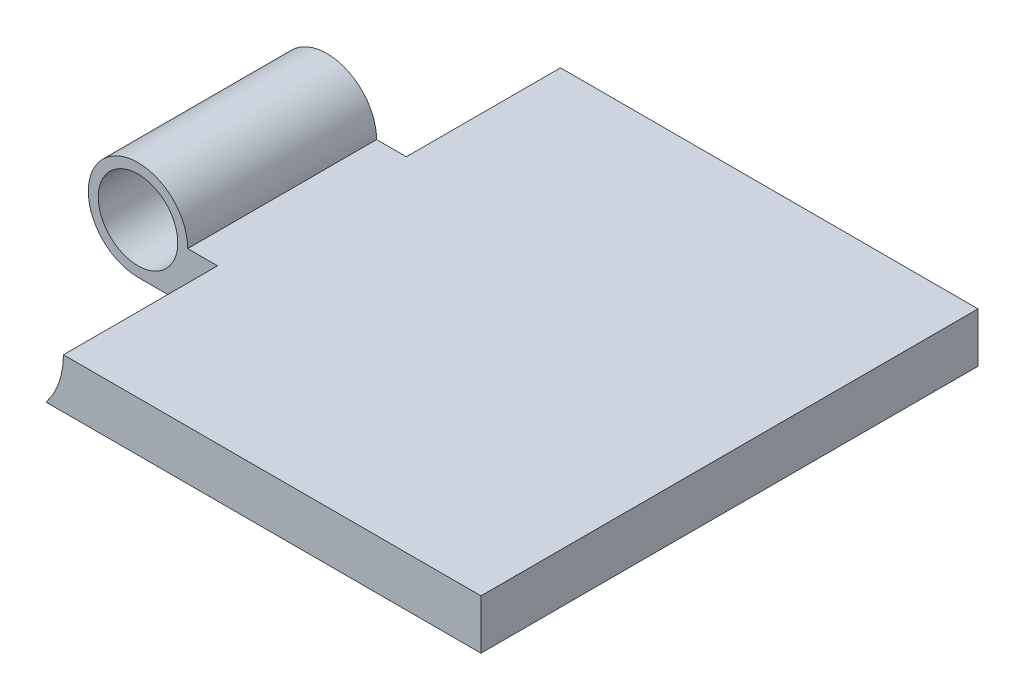
SolidWorks part; units mm, degrees
ref_plane "Front Plane" through (0, 0, 0) normal (0, 0, 1) x (1, 0, 0)
ref_plane "Top Plane" through (0, 0, 0) normal (0, 1, 0) x (1, 0, 0)
ref_plane "Right Plane" through (0, 0, 0) normal (1, 0, 0) x (0, 0, -1)
sketch "Sketch1" plane through (0, 0, 0) normal (0, 0, 1) x (1, 0, 0)
  line L1 (0, 0) -> (50, 0)
  line L2 (0, 0) -> (0, -5)
  line L3 (0, -5) -> (50, -5)
  line L4 (50, 0) -> (50, -5)
  point P5 (0, 0)
extrude "Boss-Extrude1" add sketch "Sketch1" against normal blind 50 contours L3 L4 L1 L2
sketch "Sketch2" plane through (0, 0, 0) normal (0, 0, 1) x (1, 0, 0)
  circle A0 centre (0, 0) radius 8
extrude "Cut-Extrude1" cut sketch "Sketch2" against normal blind 50 contours A0
ref_plane "Plane1" through (0, 0, -15.5) normal (0, 0, -1) x (-1, 0, 0)
sketch "Sketch3" plane through (0, 0, -15.5) normal (0, 0, -1) x (-1, 0, 0)
  circle A0 centre (0, 0) radius 5
  circle A1 centre (0, 0) radius 4
  dimension "D1" = 1
extrude "Boss-Extrude2" add sketch "Sketch3" along normal blind 19 separate body
sketch "Sketch8" plane through (0, 0, -34.5) normal (0, 0, -1) x (-1, 0, 0)
  line L1 (-4, 0) -> (-10, 0)
  line L2 (0, -4) -> (0, -5)
  line L3 (0, -5) -> (-10, -5)
  line L4 (-10, 0) -> (-10, -5)
  arc A0 (-4, 0) -> (0, -4) centre (0, 0) ccw
extrude "Boss-Extrude4" add sketch "Sketch8" against normal blind 19 contours L1 L4 L3 L2 A0
